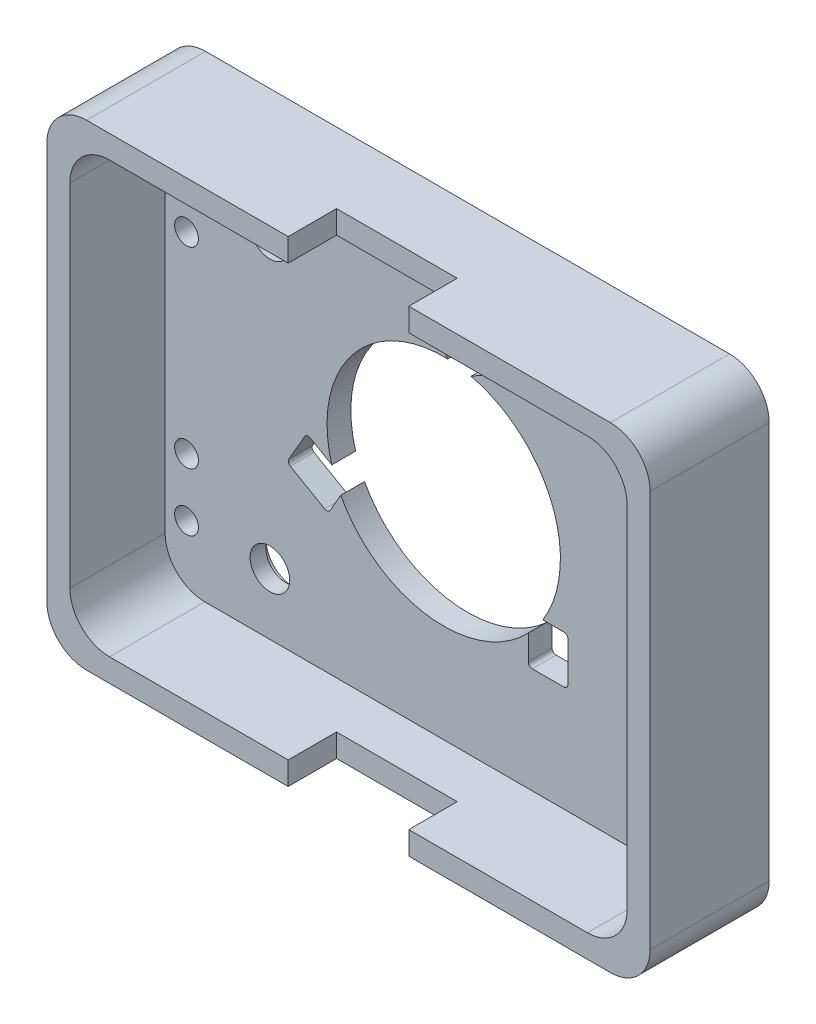
SolidWorks part; units mm, degrees
ref_plane "前基準面" through (0, 0, 0) normal (0, 0, 1) x (1, 0, 0)
ref_plane "上基準面" through (0, 0, 0) normal (0, 1, 0) x (1, 0, 0)
ref_plane "右基準面" through (0, 0, 0) normal (1, 0, 0) x (0, 0, -1)
sketch "草圖1" plane through (0, 0, 0) normal (0, 0, 1) x (1, 0, 0)
  line L1 (-33, 30) -> (33, 30)
  line L2 (-38, 25) -> (-38, -25)
  line L3 (-33, -30) -> (33, -30)
  line L4 (38, 25) -> (38, -25)
  line L5 (-38, 30) -> (38, -30) construction
  line L6 (-38, -30) -> (38, 30) construction
  arc A0 (-38, -25) -> (-33, -30) centre (-33, -25) ccw
  arc A1 (33, -30) -> (38, -25) centre (33, -25) ccw
  arc A2 (33, 30) -> (38, 25) centre (33, 25) cw
  arc A3 (-33, 30) -> (-38, 25) centre (-33, 25) ccw
  point P0 (0, 0)
  dimension "D3" = 5
  dimension "D1" = 76
  dimension "D2" = 60
extrude "填料-伸長1" add sketch "草圖1" along normal blind 15
sketch "草圖2" plane through (0, 0, 15) normal (0, 0, 1) x (1, 0, 0)
  line L0 (33, 30) -> (-33, 30) construction
  line L1 (-30.1, 27.1) -> (30.1, 27.1)
  line L2 (-35.1, 22.1) -> (-35.1, -22.1)
  line L3 (-30.1, -27.1) -> (30.1, -27.1)
  line L4 (35.1, 22.1) -> (35.1, -22.1)
  line L5 (-35.1, 27.1) -> (35.1, -27.1) construction
  line L6 (-35.1, -27.1) -> (35.1, 27.1) construction
  line L8 (-38, 25) -> (-38, -25) construction
  arc A0 (-35.1, -22.1) -> (-30.1, -27.1) centre (-30.1, -22.1) ccw
  arc A1 (30.1, -27.1) -> (35.1, -22.1) centre (30.1, -22.1) ccw
  arc A2 (30.1, 27.1) -> (35.1, 22.1) centre (30.1, 22.1) cw
  arc A3 (-30.1, 27.1) -> (-35.1, 22.1) centre (-30.1, 22.1) ccw
  point P0 (0, 0)
  dimension "D3" = 5
  dimension "D1" = 2.9
  dimension "D2" = 2.9
extrude "除料-伸長1" cut sketch "草圖2" against normal blind 12
sketch "草圖3" plane through (0, 0, 0) normal (0, 1, 0) x (1, 0, 0)
  line L0 (0, 11.6056) -> (0, -27.4941) construction
  line L1 (0, -3) -> (14.7, -3)
  line L2 (30.1, -3) -> (-30.1, -3) construction
  line L3 (14.7, -3) -> (14.7, -1.9)
  line L6 (0, -1.9) -> (0, -3)
  line L7 (14.7, -1.9) -> (14.7, 0)
  line L8 (33, 0) -> (-33, 0) construction
  line L9 (14.7, 0) -> (0, 0)
  line L10 (0, 0) -> (0, -1.9)
  dimension "D1" = 14.7
  dimension "D2" = 14.7
  dimension "D3" = 1.1
revolve "除料-旋轉1" cut sketch "草圖3" angle 360 about L0
ref_plane "平面1" through (0, 0, 15) normal (0, 0, 1) x (1, 0, 0)
sketch "草圖4" plane through (0, 0, 15) normal (0, 0, 1) x (1, 0, 0)
  line L0 (0, 32.9941) -> (0, -32.6269) construction
  line L1 (-42.1259, 0) -> (41.8506, 0) construction
  line L2 (7.6, 30) -> (-7.6, 30)
  line L3 (33, 30) -> (-33, 30) construction
  line L4 (-7.6, 30) -> (-7.6, 27.1)
  line L5 (30.1, 27.1) -> (-30.1, 27.1) construction
  line L6 (-7.6, 27.1) -> (7.6, 27.1)
  line L7 (30.1, 27.1) -> (-30.1, 27.1) construction
  line L8 (0, 27.1) -> (0, 30)
  line L9 (7.6, 30) -> (7.6, 27.1)
  line L10 (-7.6, -30) -> (-7.6, -27.1)
  line L11 (7.6, -30) -> (-7.6, -30)
  line L12 (7.6, -30) -> (7.6, -27.1)
  line L13 (-7.6, -27.1) -> (7.6, -27.1)
  dimension "D1" = 7.6
extrude "除料-伸長2" cut sketch "草圖4" against normal blind 6.1 contours L6 L9 L2 L4 | L11 L10 L13 L12
sketch "草圖5" plane through (0, 0, 3) normal (0, 0, 1) x (1, 0, 0)
  line L0 (0, 27.1) -> (0, -27.1) construction
  line L1 (30.1, 27.1) -> (-30.1, 27.1) construction
  line L2 (-7.6, -27.1) -> (7.6, -27.1) construction
  line L3 (-35.1, 0) -> (35.1, 0) construction
  line L4 (-35.1, 22.1) -> (-35.1, -22.1) construction
  line L5 (35.1, -22.1) -> (35.1, 22.1) construction
  line L6 (-35.1, 22.1) -> (-25.1, 22.1) construction
  line L7 (-25.1, 22.1) -> (-25.1, -22.1) construction
  line L8 (-25.1, -22.1) -> (-35.1, -22.1) construction
  line L9 (-35.1, 22.1) -> (-35.1, -22.1) construction
  line L10 (35.1, -22.1) -> (35.1, 22.1) construction
  line L11 (13.15, 0) -> (13.15, -16.56) construction
  line L12 (11.15, -8.28) -> (15.15, -8.28) construction
  line L13 (11.15, -7.78) -> (15.15, -7.78) construction
  line L14 (15.15, -7.78) -> (15.15, -8.78) construction
  line L15 (15.15, -8.78) -> (11.15, -8.78) construction
  line L16 (11.15, -8.78) -> (11.15, -7.78) construction
  line L17 (0, 0) -> (-14.4458, 25.0209) construction
  line L18 (-6.575, 11.3882) -> (6.9004, 19.1682) construction
  line L19 (-0.8373, 17.0103) -> (1.1627, 13.5462) construction
  line L20 (-0.8373, 17.0103) -> (0.0287, 17.5103) construction
  line L21 (0.0287, 17.5103) -> (2.0287, 14.0462) construction
  line L22 (2.0287, 14.0462) -> (1.1627, 13.5462) construction
  line L23 (-0.4043, 17.2603) -> (1.5957, 13.7962) construction
  line L24 (0, 0) -> (-14.6172, -25.3177) construction
  line L25 (-6.575, -11.3882) -> (-20.0504, -3.6082) construction
  line L30 (-12.3127, -5.7662) -> (-14.3127, -9.2303) construction
  line L31 (-12.3127, -5.7662) -> (-13.1787, -5.2662) construction
  line L32 (-13.1787, -5.2662) -> (-15.1787, -8.7303) construction
  line L33 (-15.1787, -8.7303) -> (-14.3127, -9.2303) construction
  line L34 (-12.7457, -5.5162) -> (-14.7457, -8.9803) construction
  line L35 (-17.5088, -2.7662) -> (-19.5088, -6.2303) construction
  line L36 (-19.5088, -6.2303) -> (-18.6428, -6.7303) construction
  line L37 (-16.6428, -3.2662) -> (-18.6428, -6.7303) construction
  line L38 (-16.6428, -3.2662) -> (-17.5088, -2.7662) construction
  line L39 (-17.0758, -3.0162) -> (-19.0758, -6.4803) construction
  line L40 (-19.3258, -6.9133) -> (-14.9957, -9.4133)
  line L41 (-16.8258, -2.5832) -> (-12.4957, -5.0832)
  line L42 (-17.5088, -2.7662) -> (-19.5088, -6.2303)
  line L43 (-12.3127, -5.7662) -> (-14.3127, -9.2303)
  line L44 (3.4928, 19.5103) -> (5.4928, 16.0462) construction
  line L45 (6.3588, 16.5462) -> (5.4928, 16.0462) construction
  line L46 (3.4928, 19.5103) -> (4.3588, 20.0103) construction
  line L47 (4.3588, 20.0103) -> (6.3588, 16.5462) construction
  line L48 (3.9258, 19.7603) -> (5.9258, 16.2962) construction
  line L49 (-0.6543, 17.6933) -> (3.6758, 20.1933)
  line L50 (6.1758, 15.8632) -> (1.8457, 13.3632)
  line L51 (4.3588, 20.0103) -> (6.3588, 16.5462)
  line L52 (-0.8373, 17.0103) -> (1.1627, 13.5462)
  line L53 (11.15, -13.78) -> (11.15, -12.78) construction
  line L54 (15.15, -13.78) -> (11.15, -13.78) construction
  line L55 (15.15, -12.78) -> (15.15, -13.78) construction
  line L56 (11.15, -12.78) -> (15.15, -12.78) construction
  line L57 (11.15, -13.28) -> (15.15, -13.28) construction
  line L58 (11.15, -7.78) -> (15.15, -7.78)
  line L59 (15.15, -13.78) -> (11.15, -13.78)
  line L60 (15.65, -8.28) -> (15.65, -13.28)
  line L61 (10.65, -8.28) -> (10.65, -13.28)
  circle A0 centre (-32.4, 19.4) radius 1.5
  circle A1 centre (32.4, 17.9) radius 1.5
  circle A2 centre (-32.4, -19.4) radius 1.5
  circle A3 centre (32.4, -19.4) radius 1.5
  circle A4 centre (11.15, -8.28) radius 0.5 construction
  circle A5 centre (15.15, -8.28) radius 0.5 construction
  circle A6 centre (-0.4043, 17.2603) radius 0.5 construction
  circle A7 centre (1.5957, 13.7962) radius 0.5 construction
  circle A8 centre (-12.7457, -5.5162) radius 0.5 construction
  circle A9 centre (-14.7457, -8.9803) radius 0.5 construction
  circle A10 centre (-19.0758, -6.4803) radius 0.5 construction
  circle A11 centre (-17.0758, -3.0162) radius 0.5 construction
  arc A12 (-16.8258, -2.5832) -> (-17.5088, -2.7662) centre (-17.0758, -3.0162) ccw
  arc A13 (-19.5088, -6.2303) -> (-19.3258, -6.9133) centre (-19.0758, -6.4803) ccw
  arc A14 (-14.9957, -9.4133) -> (-14.3127, -9.2303) centre (-14.7457, -8.9803) ccw
  arc A15 (-12.4957, -5.0832) -> (-12.3127, -5.7662) centre (-12.7457, -5.5162) cw
  circle A16 centre (3.9258, 19.7603) radius 0.5 construction
  circle A17 centre (5.9258, 16.2962) radius 0.5 construction
  arc A18 (-0.6543, 17.6933) -> (-0.8373, 17.0103) centre (-0.4043, 17.2603) ccw
  arc A19 (3.6758, 20.1933) -> (4.3588, 20.0103) centre (3.9258, 19.7603) cw
  arc A20 (6.3588, 16.5462) -> (6.1758, 15.8632) centre (5.9258, 16.2962) cw
  circle A21 centre (15.15, -13.28) radius 0.5 construction
  circle A22 centre (11.15, -13.28) radius 0.5 construction
  arc A23 (1.8457, 13.3632) -> (1.1627, 13.5462) centre (1.5957, 13.7962) cw
  arc A24 (11.15, -7.78) -> (10.65, -8.28) centre (11.15, -8.28) ccw
  arc A25 (10.65, -13.28) -> (11.15, -13.78) centre (11.15, -13.28) ccw
  arc A26 (15.15, -13.78) -> (15.65, -13.28) centre (15.15, -13.28) ccw
  arc A27 (15.65, -8.28) -> (15.15, -7.78) centre (15.15, -8.28) ccw
  circle A28 centre (-32.4, 12.1) radius 1.5
  circle A29 centre (32.4, 12.1) radius 1.5
  circle A30 centre (32.4, -12.1) radius 1.5
  circle A31 centre (-32.4, -12.1) radius 1.5
  point P35 (13.15, -8.28)
  point P38 (11.15, -8.28)
  point P50 (0.1627, 15.2782)
  point P62 (-13.3127, -7.4982)
  point P78 (-18.0758, -4.7482)
  point P96 (4.9258, 18.0282)
  point P106 (11.15, -13.28)
  point P112 (13.15, -13.28)
  circle M4 centre (0, 0) radius 14.7
  dimension "D2" = 3
  dimension "D6" = 3
  dimension "D8" = 13.15
  dimension "D25" = 5
  dimension "D31" = 3
  dimension "D1" = 10
  dimension "D3" = 2.7
  dimension "D4" = 2.7
  dimension "D5" = 4.2
  dimension "D7" = 2.7
  dimension "D9" = 4
  dimension "D10" = 1
  dimension "D11" = 7.78
  dimension "D12" = 120
  dimension "D13" = 13.15
  dimension "D14" = 4
  dimension "D15" = 1
  dimension "D16" = 7.78
  dimension "D17" = 120
  dimension "D18" = 13.15
  dimension "D19" = 4
  dimension "D20" = 1
  dimension "D21" = 7.78
  dimension "D22" = 5
  dimension "D23" = 4
  dimension "D24" = 1
  dimension "D26" = 1
  dimension "D27" = 4
  dimension "D28" = 5
  dimension "D29" = 4
  dimension "D30" = 1
  dimension "D32" = 15
extrude "除料-伸長3" cut sketch "草圖5" against normal through all contours L31 A8 | L31 A8 | L20 A6 | L20 A6 | L22 A7 | L22 A7 | A20 L51 A19 L49 A18 L52 L50 M4 | A23 L50 L52 M4 | L40 A14 L43 L41 A12 L42 A13 M4 | A30 | A0 | A2 | A3 | A1 | L61 A25 L59 A26 L60 A27 L58 A24 | A28 | A31 | A29
sketch "草圖8" plane through (0, 0, 3) normal (0, 0, 1) x (1, 0, 0)
  line L0 (-30.1, -27.1) -> (30.1, -27.1) construction
  line L1 (30.1, 27.1) -> (-30.1, 27.1) construction
  line L2 (35.1, -22.1) -> (35.1, 22.1) construction
  line L3 (0, 27.1) -> (0, -27.1) construction
  line L4 (-7.6, 27.1) -> (7.6, 27.1) construction
  line L5 (-7.6, -27.1) -> (7.6, -27.1) construction
  circle A0 centre (-21.9, -19.4) radius 2.5
  circle A2 centre (21.9, 16.9) radius 2.5
  circle A3 centre (-21.9, 16.9) radius 2.5
  dimension "D2" = 5
  dimension "D3" = 10.2
  dimension "D5" = 5
  dimension "D1" = 7.7
  dimension "D4" = 13.2
extrude "除料-伸長4" cut sketch "草圖8" against normal through all
sketch "草圖9" plane through (0, 0, 0) normal (0, 0, -1) x (-1, 0, 0)
  circle A0 centre (-21.9, 16.9) radius 3.5
  circle A1 centre (21.9, -19.4) radius 3.5
  circle A2 centre (21.9, 16.9) radius 4
  dimension "D1" = 7
  dimension "D2" = 7
  dimension "D3" = 8
extrude "除料-伸長6" cut sketch "草圖9" against normal blind 1
